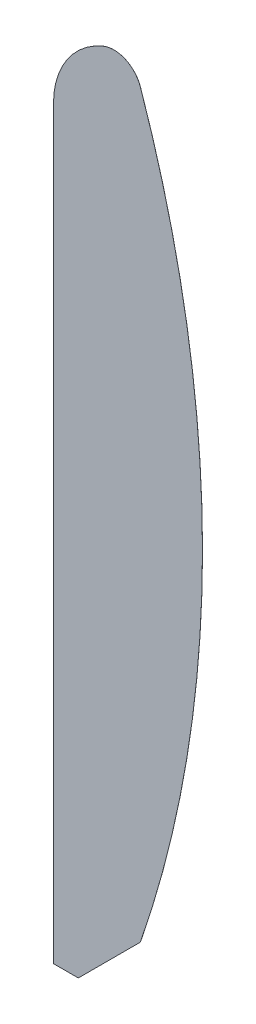
SolidWorks part; units mm, degrees
ref_plane "Front Plane" through (0, 0, 0) normal (1, 0, 0) x (0, 1, 0)
ref_plane "Top Plane" through (0, 0, 0) normal (0, 0, 1) x (0, 1, 0)
ref_plane "Right Plane" through (0, 0, 0) normal (0, 1, 0) x (-1, 0, 0)
sketch "Sketch1" plane through (0, 0, 0) normal (0, 0, 1) x (0, 1, 0)
  line L0 (0, 0) -> (0, 46433.2994) construction
  line L1 (0, 0) -> (-46433.2994, 0) construction
  line L2 (341.0561, 447.2498) -> (1519.4065, 281.6435) construction
  line L3 (0, 0) -> (150, 0)
  line L9 (0, 0) -> (0, -5)
  line L10 (0, -5) -> (12.5, -17.5)
  line L11 (0, 0) -> (87.0667, -30)
  arc A0 (150, 0) -> (165, -10) centre (150, -16.25) cw
  arc A1 (165, -10) -> (161.6335, -17.5) centre (159.7945, -12.169) cw
  arc A2 (12.5, -17.5) -> (161.6335, -17.5) centre (87.0667, 198.658) ccw
  dimension "D1" = 150
  dimension "D2" = 5
  dimension "D3" = 30
  dimension "D4" = 17.5
  dimension "D5" = 165
  dimension "D6" = 12.5
  dimension "D7" = 10
extrude "Boss-Extrude1" add sketch "Sketch1" along normal blind 0.01 contours L3 A0 A1 A2 L10 L9
